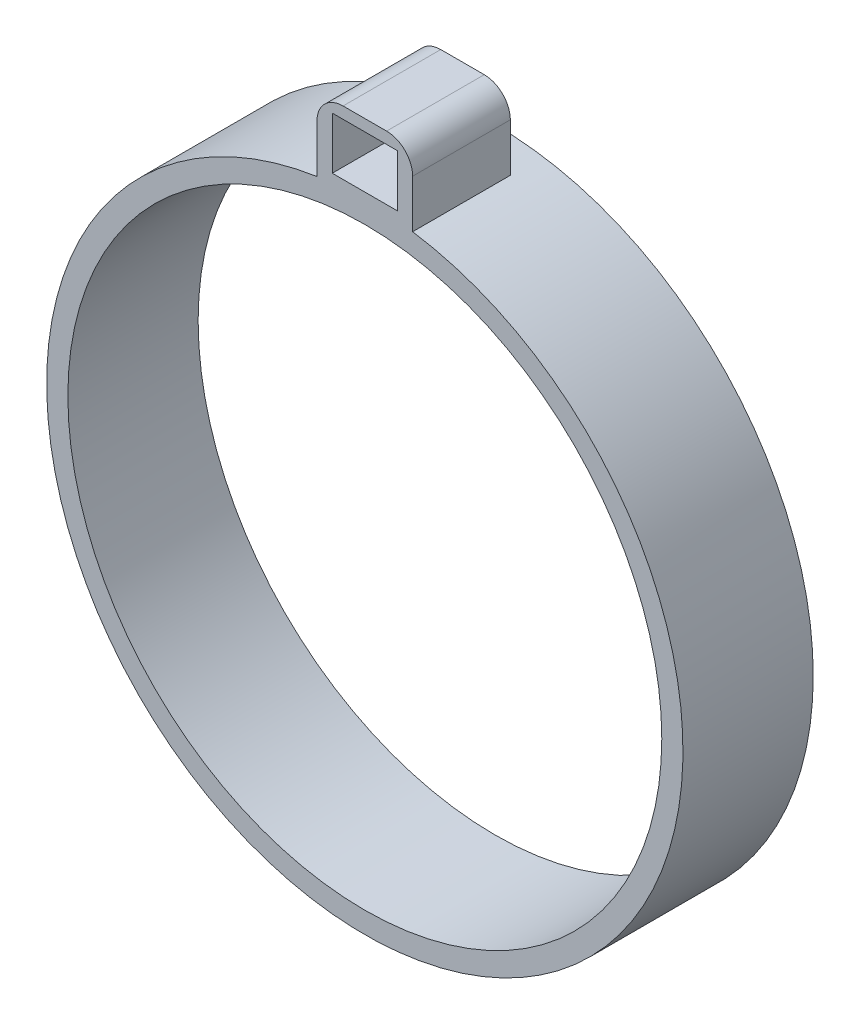
SolidWorks part; units mm, degrees
material "ABS PC"
ref_plane "Front Plane" through (0, 0, 0) normal (0, 0, 1) x (1, 0, 0)
ref_plane "Top Plane" through (0, 0, 0) normal (0, 1, 0) x (1, 0, 0)
ref_plane "Right Plane" through (0, 0, 0) normal (1, 0, 0) x (0, 0, -1)
sketch "Sketch1" plane through (0, 0, 0) normal (0, 0, 1) x (1, 0, 0)
  circle A0 centre (0, 0) radius 45.5931
  circle A1 centre (0, 0) radius 48.8466
extrude "Boss-Extrude1" add sketch "Sketch1" along normal mid plane 20
sketch "Sketch2" plane through (0, 0, 10) normal (0, 0, 1) x (1, 0, 0)
  line L1 (-5, 57.8998) -> (5, 57.8998)
  line L2 (-5, 57.8998) -> (-5, 49.8998)
  line L3 (-5, 49.8998) -> (5, 49.8998)
  line L4 (5, 57.8998) -> (5, 49.8998)
  line L5 (-5, 57.8998) -> (5, 49.8998) construction
  line L6 (-5, 49.8998) -> (5, 57.8998) construction
  line L7 (-7.3411, 59.6748) -> (7.3411, 59.6748)
  line L8 (-7.3411, 59.6748) -> (-7.3411, 48.1248)
  line L9 (-7.3411, 48.1248) -> (7.3411, 48.1248)
  line L10 (7.3411, 59.6748) -> (7.3411, 48.1248)
  line L11 (-7.3411, 59.6748) -> (7.3411, 48.1248) construction
  line L12 (-7.3411, 48.1248) -> (7.3411, 59.6748) construction
  point P0 (0, 53.8998)
  point P5 (0, 53.8998)
  point P10 (-0.515, 52.5317)
  point P12 (-7.3411, 59.6748)
  dimension "D1" = 8
  dimension "D2" = 10
extrude "Boss-Extrude2" add sketch "Sketch2" against normal blind 15
fillet "Fillet1" radius 4 2 edges at (7.3411, 59.6748, 2.5) (-7.3411, 59.6748, 2.5)
